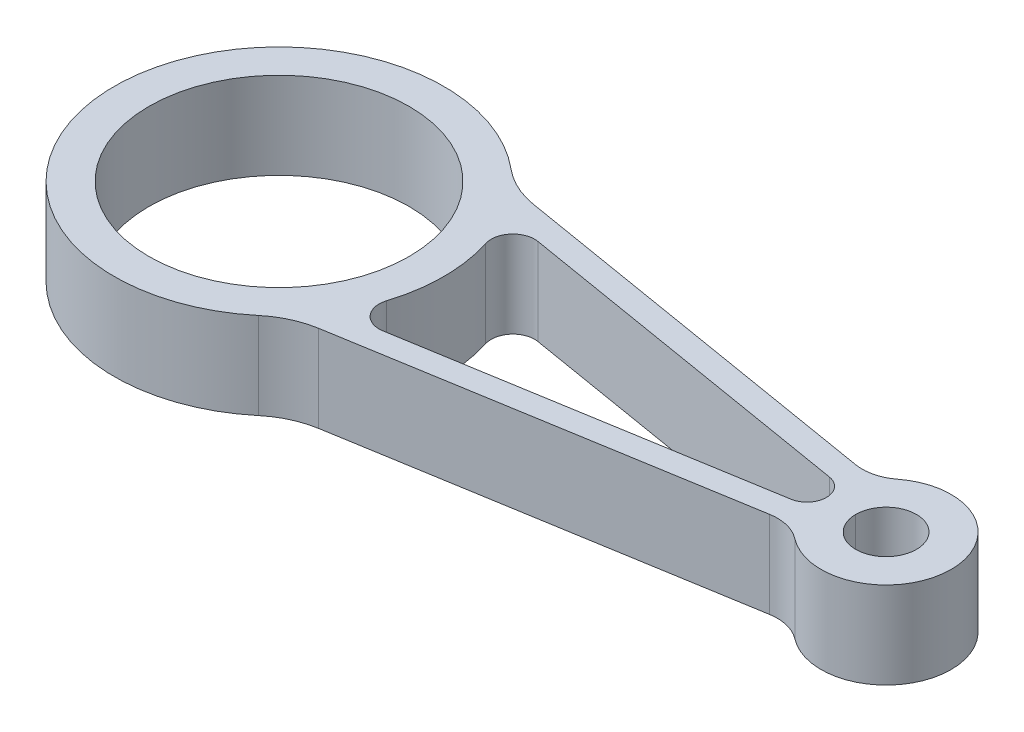
SolidWorks part; units mm, degrees
material "Plain Carbon Steel"
ref_plane "Front Plane" through (0, 0, 0) normal (0, 0, 1) x (1, 0, 0)
ref_plane "Top Plane" through (0, 0, 0) normal (0, 1, 0) x (1, 0, 0)
ref_plane "Right Plane" through (0, 0, 0) normal (1, 0, 0) x (0, 0, -1)
sketch "Sketch1" plane through (0, 0, 0) normal (0, 1, 0) x (1, 0, 0)
  line L0 (-48.1342, 0) -> (171.6981, 0) construction
  line L1 (27.9355, 25.7606) -> (128.0638, 9.0844)
  line L2 (128.0638, -9.0844) -> (27.9355, -25.7606)
  circle A0 centre (0, 0) radius 30
  circle A1 centre (140, 0) radius 7
  arc A2 (27.9355, 25.7606) -> (27.9355, -25.7606) centre (0, 0) ccw
  arc A3 (128.0638, -9.0844) -> (128.0638, 9.0844) centre (140, 0) ccw
  arc A4 (38, 0) -> (27.9355, 25.7606) centre (0, 0) ccw construction
  arc A5 (27.9355, -25.7606) -> (38, 0) centre (0, 0) ccw construction
  arc A6 (128.0638, 9.0844) -> (125, 0) centre (140, 0) ccw construction
  arc A7 (125, 0) -> (128.0638, -9.0844) centre (140, 0) ccw construction
  dimension "D2" = 14
  dimension "D3" = 60
  dimension "D4" = 76
  dimension "D5" = 30
  dimension "D1" = 140
extrude "Boss-Extrude1" add sketch "Sketch1" along normal mid plane 20
fillet "Fillet1" radius 10 2 edges at (128.0638, 0, 9.0844) (128.0638, 0, -9.0844)
fillet "Fillet2" radius 20 2 edges at (27.9355, 0, 25.7606) (27.9355, 0, -25.7606)
sketch "Sketch2" plane through (0, 10, 0) normal (0, 1, 0) x (1, 0, 0)
  line L0 (-7.1874, 0) -> (164.9095, 0) construction
  line L1 (41.8286, 17.871) -> (122.4784, 4.4389)
  line L2 (122.3109, -4.4635) -> (41.652, -17.8972)
  line L4 (123.0688, 9.9163) -> (33.9231, 24.7634) construction
  line L5 (33.9231, -24.7634) -> (123.0688, -9.9163) construction
  arc A0 (41.8286, 17.871) -> (36.2389, 11.4344) centre (41.0071, 12.9389) ccw
  arc A1 (36.2389, 11.4344) -> (36.2389, -11.4344) centre (0, 0) cw
  arc A2 (36.2389, -11.4344) -> (41.652, -17.8972) centre (41.0071, -12.9389) ccw
  arc A3 (122.4784, 4.4389) -> (122.3109, -4.4635) centre (121.7391, 0) cw
  circle A4 centre (0, 0) radius 30 construction
  point P13 (0, 0)
  point P18 (0, 0)
  point P21 (36.2389, -23.6375)
  point P22 (41.0775, -12.9936)
  point P23 (0, 0)
  point P24 (0, 0)
  dimension "D1" = 5
  dimension "D2" = 4.5
  dimension "D5" = 8
  dimension "D3" = 5.5
  dimension "D4" = 5.5032
extrude "Cut-Extrude1" cut sketch "Sketch2" against normal through all
split line "Split Line4"
